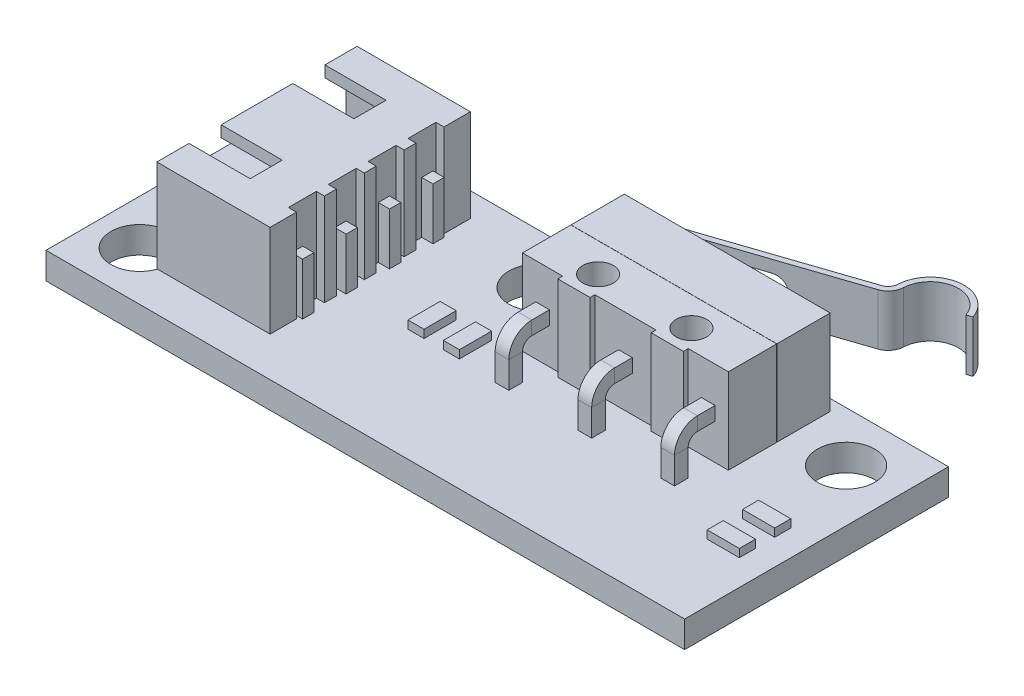
SolidWorks part; units mm, degrees
ref_plane "Front Plane" through (0, 0, 0) normal (0, 0, 1) x (1, 0, 0)
ref_plane "Top Plane" through (0, 0, 0) normal (0, 1, 0) x (1, 0, 0)
ref_plane "Right Plane" through (0, 0, 0) normal (1, 0, 0) x (0, 0, -1)
sketch "Sketch1" plane through (0, 0, 0) normal (0, 1, 0) x (1, 0, 0)
  line L1 (-19.85, -8.2) -> (19.85, -8.2)
  line L2 (-19.85, -8.2) -> (-19.85, 8.2)
  line L3 (-19.85, 8.2) -> (19.85, 8.2)
  line L4 (19.85, -8.2) -> (19.85, 8.2)
  line L5 (-19.85, -8.2) -> (19.85, 8.2) construction
  line L6 (-19.85, 8.2) -> (19.85, -8.2) construction
  point P0 (0, 0)
  dimension "D1" = 39.7
  dimension "D2" = 16.4
extrude "Boss-Extrude1" add sketch "Sketch1" along normal blind 1.65
sketch "Sketch2" plane through (0, 1.65, 0) normal (0, 1, 0) x (1, 0, 0)
  line L0 (19.85, -8.2) -> (19.85, 8.2) construction
  line L1 (13.2, 7.5) -> (0.4, 7.5)
  line L2 (13.2, 7.5) -> (13.2, 0.87)
  line L3 (13.2, 0.87) -> (0.4, 0.87)
  line L4 (0.4, 7.5) -> (0.4, 0.87)
  line L5 (19.85, 8.2) -> (-19.85, 8.2) construction
  dimension "D1" = 6.65
  dimension "D2" = 12.8
  dimension "D3" = 0.7
  dimension "D4" = 6.63
extrude "Boss-Extrude2" add sketch "Sketch2" along normal blind 5.3
sketch "Sketch3" plane through (0, 6.95, 0) normal (0, 1, 0) x (1, 0, 0)
  line L0 (0.4, 0.87) -> (13.2, 0.87) construction
  line L1 (0.4, 0.87) -> (2.9, 0.87)
  line L2 (0.4, 0.87) -> (0.4, 1.17)
  line L3 (0.4, 1.17) -> (2.9, 1.17)
  line L4 (2.9, 0.87) -> (2.9, 1.17)
  line L5 (4.9, 0.87) -> (8.7, 0.87)
  line L6 (4.9, 0.87) -> (4.9, 1.17)
  line L7 (4.9, 1.17) -> (8.7, 1.17)
  line L8 (8.7, 0.87) -> (8.7, 1.17)
  line L9 (0.4, 7.5) -> (0.4, 0.87) construction
  line L10 (13.2, 0.87) -> (10.7, 0.87)
  line L11 (13.2, 0.87) -> (13.2, 1.17)
  line L12 (13.2, 1.17) -> (10.7, 1.17)
  line L13 (10.7, 0.87) -> (10.7, 1.17)
  line L14 (0.4, 4.185) -> (13.2, 4.185)
  line L15 (0.4, 4.185) -> (0.4, 4.175)
  line L16 (0.4, 4.175) -> (13.2, 4.175)
  line L17 (13.2, 4.185) -> (13.2, 4.175)
  line L18 (13.2, 0.87) -> (13.2, 7.5) construction
  point P24 (6.8, 0.87)
  point P26 (6.8, 1.17)
  dimension "D1" = 0.01
  dimension "D2" = 3.8
  dimension "D3" = 0.3
  dimension "D4" = 2
  dimension "D5" = 2
extrude "Cut-Extrude1" cut sketch "Sketch3" against normal up to surface (5.3 mm away) up to face at (0, 1.65, 0)
sketch "Sketch4" plane through (0, 6.95, 0) normal (0, 1, 0) x (1, 0, 0)
  line L0 (2.9, 0.87) -> (4.9, 0.87) construction
  line L1 (8.7, 0.87) -> (10.7, 0.87) construction
  circle A0 centre (3.9, 2.37) radius 0.95
  circle A1 centre (9.7, 2.37) radius 0.95
  point P6 (3.9, 0.87)
  point P9 (9.7, 0.87)
  dimension "D1" = 1.9
  dimension "D2" = 1.5
extrude "Cut-Extrude2" cut sketch "Sketch4" against normal up to surface (5.3 mm away) up to face at (6.8, 1.65, -5.8425)
sketch "Sketch5" plane through (0, 6.95, 0) normal (0, 1, 0) x (1, 0, 0)
  line L0 (4.4, 7.5) -> (4.4, 7.75) construction
  line L1 (13.2, 7.5) -> (0.4, 7.5) construction
  line L2 (3.65, 7.5) -> (3.65, 7.75)
  line L3 (5.15, 7.5) -> (5.15, 7.75)
  line L4 (0.4, 7.5) -> (0.4, 4.185) construction
  line L5 (13.2, 7.5) -> (0.4, 7.5) construction
  arc A0 (3.65, 7.5) -> (5.15, 7.5) centre (4.4, 7.5) ccw
  arc A1 (5.15, 7.75) -> (3.65, 7.75) centre (4.4, 7.75) ccw
  point P4 (4.4, 7.625)
  point P11 (4.4, 8.5)
  dimension "D1" = 4
  dimension "D2" = 1
  dimension "D3" = 1.5
extrude "Boss-Extrude3" add sketch "Sketch5" against normal blind 3 from offset 1.1 offset against normal yes
sketch "Sketch6" plane through (0, 6.95, 0) normal (0, 1, 0) x (1, 0, 0)
  line L0 (1.3031, 7.5) -> (12.4306, 11.2413)
  line L1 (13.2, 7.5) -> (0.4, 7.5) construction
  line L2 (13.2, 11.5) -> (16.5175, 12.6154) construction
  line L3 (13.2, 4.185) -> (13.2, 7.5) construction
  line L5 (1.3031, 7.5) -> (0.8291, 7.3407)
  arc A0 (16.5175, 12.6154) -> (13.1108, 12.1414) centre (14.8588, 12.0577) ccw
  arc A1 (5.15, 7.75) -> (3.65, 7.75) centre (4.4, 7.75) ccw construction
  arc A2 (12.4306, 11.2413) -> (13.1108, 12.1414) centre (12.1119, 12.1892) ccw
  dimension "D2" = 1.75
  dimension "D3" = 1
  dimension "D1" = 4
  dimension "D4" = 0.5
extrude "Extrude-Thin1" add sketch "Sketch6" against normal blind 3.2 from offset 1 separate body thin thin type one direction wall 0.35 offset against normal yes
sketch "Sketch7" plane through (0, 1.65, 0) normal (0, 1, 0) x (1, 0, 0)
  line L0 (-19.85, -8.2) -> (19.85, -8.2) construction
  line L1 (-15.41, 6.7) -> (-8.37, 6.7)
  line L2 (-15.41, 6.7) -> (-15.41, -5.75)
  line L3 (-15.41, -5.75) -> (-8.37, -5.75)
  line L4 (-8.37, 6.7) -> (-8.37, -5.75)
  line L6 (-19.85, 8.2) -> (-19.85, -8.2) construction
  dimension "D1" = 2.45
  dimension "D2" = 12.45
  dimension "D3" = 7.04
  dimension "D4" = 4.44
extrude "Boss-Extrude4" add sketch "Sketch7" along normal blind 5.75
sketch "Sketch8" plane through (0, 0, 0) normal (0, -1, 0) x (1, 0, 0)
  line L0 (19.85, 8.2) -> (19.85, -8.2) construction
  line L1 (19.85, -8.2) -> (-19.85, -8.2) construction
  line L2 (-19.85, -8.2) -> (-19.85, 8.2) construction
  circle A0 centre (16.6125, -5.0725) radius 1.7875
  circle A1 centre (-2.5625, -5.0725) radius 1.7875
  circle A2 centre (-17.0625, -5.6125) radius 1.7875
  circle A3 centre (-17.0625, 5.1625) radius 1.7875
  point P8 (16.6125, -6.86)
  point P9 (18.4, -5.0725)
  point P10 (-2.5625, -6.86)
  point P11 (-4.35, -5.0725)
  point P12 (-17.0625, -7.4)
  point P13 (-18.85, -5.6125)
  point P14 (-18.85, 5.1625)
  point P15 (-17.0625, 6.95)
  point P20 (14.825, -5.0725)
  point P21 (-0.775, -5.0725)
  point P24 (-17.0625, 3.375)
  point P25 (-17.0625, -3.825)
  dimension "D1" = 3.575
  dimension "D2" = 1.45
  dimension "D3" = 1.34
  dimension "D4" = 19.175
  dimension "D5" = 0.8
  dimension "D6" = 1
  dimension "D7" = 7.2
extrude "Cut-Extrude3" cut sketch "Sketch8" against normal up to surface (1.65 mm away) up to face at (6.8, 1.65, -1.5708)
sketch "Sketch10" plane through (-15.41, 0, 0) normal (-1, 0, 0) x (0, 0, 1)
  line L0 (5.75, 7.4) -> (5.75, 1.65) construction
  line L1 (-6, 2.35) -> (5.05, 2.35)
  line L2 (-6, 2.35) -> (-6, 6.7)
  line L3 (-6, 6.7) -> (5.05, 6.7)
  line L4 (5.05, 2.35) -> (5.05, 6.7)
  line L5 (-6, 2.35) -> (5.05, 6.7) construction
  line L6 (-6, 6.7) -> (5.05, 2.35) construction
  line L7 (-6.7, 7.4) -> (5.75, 7.4) construction
  line L8 (-6.7, 7.4) -> (-6.7, 1.65) construction
  point P0 (-0.475, 4.525)
  point P9 (-0.475, 7.4)
  point P12 (-6.7, 4.525)
  dimension "D1" = 0.7
  dimension "D2" = 0.7
extrude "Cut-Extrude4" cut sketch "Sketch10" against normal offset from surface (6.04 mm away) 1 up to face at (-8.37, 4.525, -0.475)
sketch "Sketch11" plane through (0, 7.4, 0) normal (0, 1, 0) x (1, 0, 0)
  line L0 (-15.41, 4.931) -> (-15.41, -4.481) construction
  line L1 (-15.41, 4.7) -> (-11.61, 4.7)
  line L2 (-15.41, 4.7) -> (-15.41, 2.7)
  line L3 (-15.41, 2.7) -> (-11.61, 2.7)
  line L4 (-11.61, 4.7) -> (-11.61, 2.7)
  line L5 (-15.3743, -5.75) -> (-8.37, -5.75) construction
  line L6 (-15.41, -1.75) -> (-11.61, -1.75)
  line L7 (-15.41, -1.75) -> (-15.41, -3.75)
  line L8 (-15.41, -3.75) -> (-11.61, -3.75)
  line L9 (-11.61, -1.75) -> (-11.61, -3.75)
  line L10 (-8.37, 6.7) -> (-15.41, 6.7) construction
  dimension "D1" = 2
  dimension "D2" = 2
  dimension "D3" = 2
  dimension "D4" = 3.8
extrude "Cut-Extrude5" cut sketch "Sketch11" against normal up to next (0.7 mm away)
sketch "Sketch12" plane through (-9.37, 0, 0) normal (-1, 0, 0) x (0, 0, 1)
  line L0 (-6, 4.525) -> (5.05, 4.525) construction
  line L1 (-4.875, 4.875) -> (-4.175, 4.875)
  line L2 (-4.875, 4.875) -> (-4.875, 4.175)
  line L3 (-4.875, 4.175) -> (-4.175, 4.175)
  line L4 (-4.175, 4.875) -> (-4.175, 4.175)
  line L5 (-2.175, 4.875) -> (-1.475, 4.875)
  line L6 (-2.175, 4.875) -> (-2.175, 4.175)
  line L7 (-2.175, 4.175) -> (-1.475, 4.175)
  line L8 (-1.475, 4.875) -> (-1.475, 4.175)
  line L9 (0.525, 4.875) -> (1.225, 4.875)
  line L10 (0.525, 4.875) -> (0.525, 4.175)
  line L11 (0.525, 4.175) -> (1.225, 4.175)
  line L12 (1.225, 4.875) -> (1.225, 4.175)
  line L13 (3.225, 4.875) -> (3.925, 4.875)
  line L14 (3.225, 4.875) -> (3.225, 4.175)
  line L15 (3.225, 4.175) -> (3.925, 4.175)
  line L16 (3.925, 4.875) -> (3.925, 4.175)
  line L17 (-6, 2.35) -> (-6, 6.7) construction
  line L18 (5.05, 2.35) -> (5.05, 6.7) construction
  line L19 (-1.475, 4.875) -> (0.525, 4.875) construction
  line L20 (-0.475, 4.525) -> (-0.475, 4.875) construction
  line L21 (-2.175, 4.875) -> (-4.175, 4.875) construction
  line L22 (3.225, 4.875) -> (1.225, 4.875) construction
  point P22 (3.225, 4.525)
  dimension "D1" = 0.7
  dimension "D2" = 2
extrude "Boss-Extrude5" add sketch "Sketch12" along normal blind 4
chamfer "Chamfer1" distance 0.2 angle 45 16 edges at (-13.37, 4.875, 3.575) (-13.37, 4.525, 3.925) (-13.37, 4.175, 3.575) (-13.37, 4.525, 3.225) (-13.37, 4.875, 0.875) (-13.37, 4.525, 1.225) (-13.37, 4.175, 0.875) (-13.37, 4.525, 0.525) (-13.37, 4.875, -1.825) (-13.37, 4.525, -1.475) (-13.37, 4.175, -1.825) (-13.37, 4.525, -2.175) (-13.37, 4.875, -4.525) (-13.37, 4.525, -4.175) (-13.37, 4.175, -4.525) (-13.37, 4.525, -4.875)
sketch "Sketch14" plane through (0, 7.4, 0) normal (0, 1, 0) x (1, 0, 0)
  line L0 (-8.37, -5.75) -> (-8.37, 6.7) construction
  line L1 (-8.37, 5.06) -> (-8.87, 5.06)
  line L2 (-8.37, 5.06) -> (-8.37, 3.3225)
  line L3 (-8.37, 3.3225) -> (-8.87, 3.3225)
  line L4 (-8.87, 5.06) -> (-8.87, 3.3225)
  line L5 (-15.41, -5.75) -> (-8.37, -5.75) construction
  line L6 (-8.37, 2.5825) -> (-8.87, 2.5825)
  line L7 (-8.37, 2.5825) -> (-8.37, 0.845)
  line L8 (-8.37, 0.845) -> (-8.87, 0.845)
  line L9 (-8.87, 2.5825) -> (-8.87, 0.845)
  line L10 (-8.37, 0.105) -> (-8.87, 0.105)
  line L11 (-8.37, 0.105) -> (-8.37, -1.6325)
  line L12 (-8.37, -1.6325) -> (-8.87, -1.6325)
  line L13 (-8.87, 0.105) -> (-8.87, -1.6325)
  line L14 (-8.37, -2.3725) -> (-8.87, -2.3725)
  line L15 (-8.37, -2.3725) -> (-8.37, -4.11)
  line L16 (-8.37, -4.11) -> (-8.87, -4.11)
  line L17 (-8.87, -2.3725) -> (-8.87, -4.11)
  line L18 (-8.37, 6.7) -> (-15.41, 6.7) construction
  dimension "D1" = 1.64
  dimension "D2" = 1.64
  dimension "D3" = 0.74
  dimension "D4" = 0.74
  dimension "D5" = 0.74
  dimension "D6" = 0.5
extrude "Cut-Extrude6" cut sketch "Sketch14" against normal up to surface (5.75 mm away) up to face at (-2.5625, 1.65, -6.86)
sketch "Sketch16" plane through (0, 0, -1.17) normal (0, 0, 1) x (1, 0, 0)
  line L0 (0.4, 4.3) -> (1.225, 4.3) construction
  line L1 (1.225, 4.725) -> (2.075, 4.725)
  line L2 (1.225, 4.725) -> (1.225, 3.875)
  line L3 (1.225, 3.875) -> (2.075, 3.875)
  line L4 (2.075, 4.725) -> (2.075, 3.875)
  line L5 (6.375, 4.725) -> (7.225, 4.725)
  line L6 (6.375, 4.725) -> (6.375, 3.875)
  line L7 (6.375, 3.875) -> (7.225, 3.875)
  line L8 (7.225, 4.725) -> (7.225, 3.875)
  line L9 (11.525, 4.725) -> (12.375, 4.725)
  line L10 (11.525, 4.725) -> (11.525, 3.875)
  line L11 (11.525, 3.875) -> (12.375, 3.875)
  line L12 (12.375, 4.725) -> (12.375, 3.875)
  line L13 (0.4, 1.65) -> (0.4, 6.95) construction
  line L14 (1.65, 4.725) -> (1.65, 6.95) construction
  line L15 (2.9, 6.95) -> (0.4, 6.95) construction
  line L16 (11.95, 4.725) -> (11.95, 6.95) construction
  line L17 (13.2, 6.95) -> (10.7, 6.95) construction
  line L18 (6.8, 4.725) -> (6.8, 6.95) construction
  line L19 (8.7, 6.95) -> (4.9, 6.95) construction
  point P20 (6.375, 4.3)
  point P21 (11.525, 4.3)
  dimension "D1" = 0.85
sketch "Sketch17" plane through (2.9, 0, 0) normal (-1, 0, 0) x (0, 0, 1)
  line L0 (-1.17, 4.3) -> (-0.07, 4.3)
  line L1 (-1.17, 4.725) -> (-1.17, 3.875) construction
  line L2 (0.93, 3.3) -> (0.93, 1.65)
  line L3 (8.2, 1.65) -> (-8.2, 1.65) construction
  arc A0 (-0.07, 4.3) -> (0.93, 3.3) centre (-0.07, 3.3) cw
  point P9 (0.93, 4.3)
  dimension "D2" = 1
  dimension "D1" = 2.1
sweep "Sweep1" add profiles "Sketch16" path "Sketch17"
sketch "Sketch18" plane through (-2.2447, 0, -6.6764) normal (-0.3187, 0, -0.9479) x (-0.9479, 0, 0.3187)
  line L0 (-3.1253, 4.35) -> (-10.1253, 4.35) construction
  line L1 (-3.1253, 2.75) -> (-3.1253, 5.95) construction
  line L2 (-3.1253, 3.5) -> (-10.1253, 3.5)
  line L3 (-3.1253, 5.2) -> (-10.1253, 5.2)
  line L4 (-3.1253, 5.2) -> (-3.1253, 3.5)
  arc A1 (-10.1253, 5.2) -> (-10.1253, 3.5) centre (-10.1253, 4.35) ccw
  point P4 (-6.6, 4.35)
  dimension "D1" = 1.7
  dimension "D2" = 7
extrude "Cut-Extrude7" cut sketch "Sketch18" against normal up to surface (0.35 mm away) up to face at (6.6299, 4.35, -9.291)
sketch "Sketch19" plane through (-8.87, 0, 0) normal (1, 0, 0) x (0, 0, -1)
  line L0 (4.875, 4.875) -> (4.675, 4.675) construction
  line L1 (-3.925, 4.875) -> (-3.225, 4.875)
  line L2 (-3.925, 4.875) -> (-3.925, -2)
  line L3 (-3.925, -2) -> (-3.225, -2)
  line L4 (-3.225, 4.875) -> (-3.225, -2)
  line L5 (-1.225, 4.875) -> (-0.525, 4.875)
  line L6 (-1.225, 4.875) -> (-1.225, -2)
  line L7 (-1.225, -2) -> (-0.525, -2)
  line L8 (-0.525, 4.875) -> (-0.525, -2)
  line L9 (1.475, 4.875) -> (2.175, 4.875)
  line L10 (1.475, 4.875) -> (1.475, -2)
  line L11 (1.475, -2) -> (2.175, -2)
  line L12 (2.175, 4.875) -> (2.175, -2)
  line L13 (4.175, 4.875) -> (4.875, 4.875)
  line L14 (4.175, 4.875) -> (4.175, -2)
  line L15 (4.175, -2) -> (4.875, -2)
  line L16 (4.875, 4.875) -> (4.875, -2)
  line L17 (4.875, 4.875) -> (4.875, 4.175) construction
  line L18 (2.175, 4.875) -> (2.175, 4.175) construction
  line L19 (1.475, 4.875) -> (2.175, 4.875) construction
  line L20 (-0.525, 4.875) -> (-0.525, 4.175) construction
  line L21 (-0.525, 4.875) -> (-0.725, 4.675) construction
  line L22 (-3.225, 4.875) -> (-3.225, 4.175) construction
  line L23 (-3.225, 4.875) -> (-3.425, 4.675) construction
  line L24 (-6.95, 0) -> (-3.375, 0) construction
  dimension "D1" = 2
extrude "Boss-Extrude6" add sketch "Sketch19" along normal blind 0.7
sketch "Sketch20" plane through (0, 0, 0) normal (0, -1, 0) x (1, 0, 0)
  line L1 (1.225, 1.355) -> (2.075, 1.355)
  line L2 (1.225, 1.355) -> (1.225, 0.505)
  line L3 (1.225, 0.505) -> (2.075, 0.505)
  line L4 (2.075, 1.355) -> (2.075, 0.505)
  line L5 (6.375, 1.355) -> (7.225, 1.355)
  line L6 (6.375, 1.355) -> (6.375, 0.505)
  line L7 (6.375, 0.505) -> (7.225, 0.505)
  line L8 (7.225, 1.355) -> (7.225, 0.505)
  line L9 (11.525, 1.355) -> (12.375, 1.355)
  line L10 (11.525, 1.355) -> (11.525, 0.505)
  line L11 (11.525, 0.505) -> (12.375, 0.505)
  line L12 (12.375, 1.355) -> (12.375, 0.505)
extrude "Boss-Extrude7" add sketch "Sketch20" along normal blind 1.6
chamfer "Chamfer2" distance 0.2 angle 45 28 edges at (11.95, -1.6, 1.355) (12.375, -1.6, 0.93) (11.95, -1.6, 0.505) (11.525, -1.6, 0.93) (6.8, -1.6, 1.355) (7.225, -1.6, 0.93) (6.8, -1.6, 0.505) (6.375, -1.6, 0.93) (1.65, -1.6, 1.355) (2.075, -1.6, 0.93) (1.65, -1.6, 0.505) (1.225, -1.6, 0.93) (-8.52, -2, -4.175) (-8.17, -2, -4.525) (-8.52, -2, -4.875) (-8.87, -2, -4.525) (-8.52, -2, -1.475) (-8.17, -2, -1.825) (-8.52, -2, -2.175) (-8.87, -2, -1.825) (-8.52, -2, 1.225) (-8.17, -2, 0.875) (-8.52, -2, 0.525) (-8.87, -2, 0.875) (-8.52, -2, 3.925) (-8.17, -2, 3.575) (-8.52, -2, 3.225) (-8.87, -2, 3.575)
sketch "Sketch21" plane through (0, 1.65, 0) normal (0, 1, 0) x (1, 0, 0)
  line L0 (-19.85, -8.2) -> (19.85, -8.2) construction
  line L1 (19.85, -8.2) -> (19.85, 8.2) construction
  line L3 (16.25, -1) -> (18.25, -1)
  line L4 (16.25, -1) -> (16.25, 0)
  line L5 (16.25, -2.2) -> (18.25, -2.2)
  line L6 (16.25, -2.2) -> (16.25, -3.2)
  line L7 (16.25, -3.2) -> (18.25, -3.2)
  line L8 (18.25, -2.2) -> (18.25, -3.2)
  line L9 (-4.35, 0.8) -> (-3.35, 0.8)
  line L10 (-4.35, 0.8) -> (-4.35, -1.2)
  line L11 (-4.35, -1.2) -> (-3.35, -1.2)
  line L12 (-3.35, 0.8) -> (-3.35, -1.2)
  line L13 (-2.15, 0.8) -> (-1.15, 0.8)
  line L14 (-2.15, 0.8) -> (-2.15, -1.2)
  line L15 (-2.15, -1.2) -> (-1.15, -1.2)
  line L16 (-1.15, 0.8) -> (-1.15, -1.2)
  line L17 (16.25, 0) -> (18.25, 0)
  line L18 (18.25, -1) -> (18.25, 0)
  dimension "D1" = 5
  dimension "D2" = 2
  dimension "D3" = 1
  dimension "D4" = 1.6
  dimension "D5" = 1.2
  dimension "D6" = 2
  dimension "D7" = 1
  dimension "D8" = 1.2
  dimension "D9" = 21
  dimension "D10" = 7
extrude "Boss-Extrude8" add sketch "Sketch21" along normal blind 0.5
